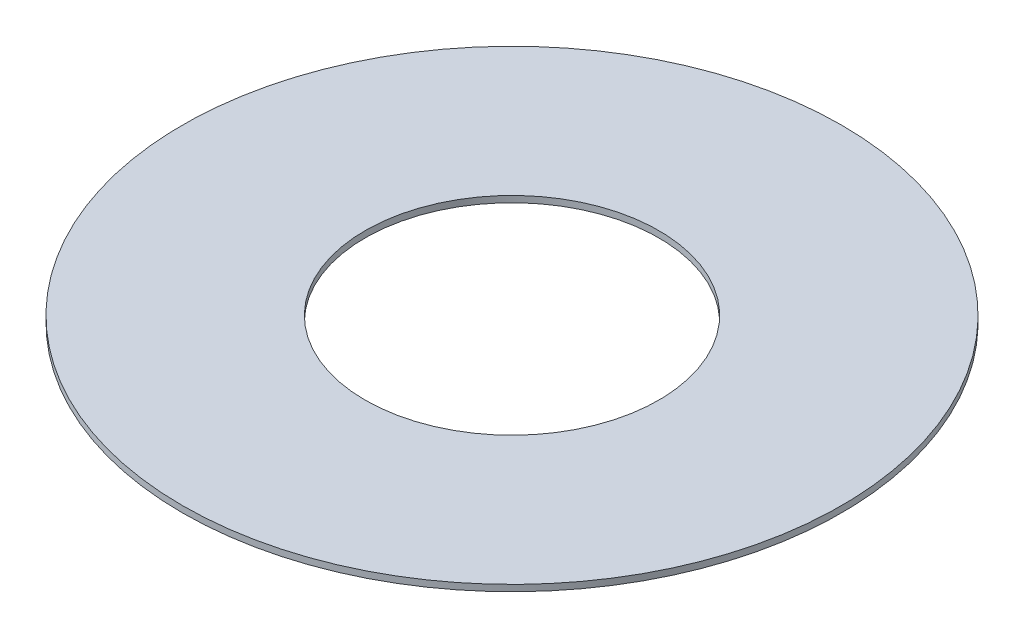
SolidWorks part; units mm, degrees
material "PTFE (general)"
ref_plane "Front Plane" through (0, 0, 0) normal (0, 0, 1) x (1, 0, 0)
ref_plane "Top Plane" through (0, 0, 0) normal (0, 1, 0) x (1, 0, 0)
ref_plane "Right Plane" through (0, 0, 0) normal (1, 0, 0) x (0, 0, -1)
sketch "Sketch1" plane through (0, 0, 0) normal (0, 1, 0) x (1, 0, 0)
  circle A0 centre (0, 0) radius 23.1
  circle A2 centre (0, 0) radius 51.838
  dimension "D1" = 46.2
extrude "Boss-Extrude1" add sketch "Sketch1" along normal blind 1
